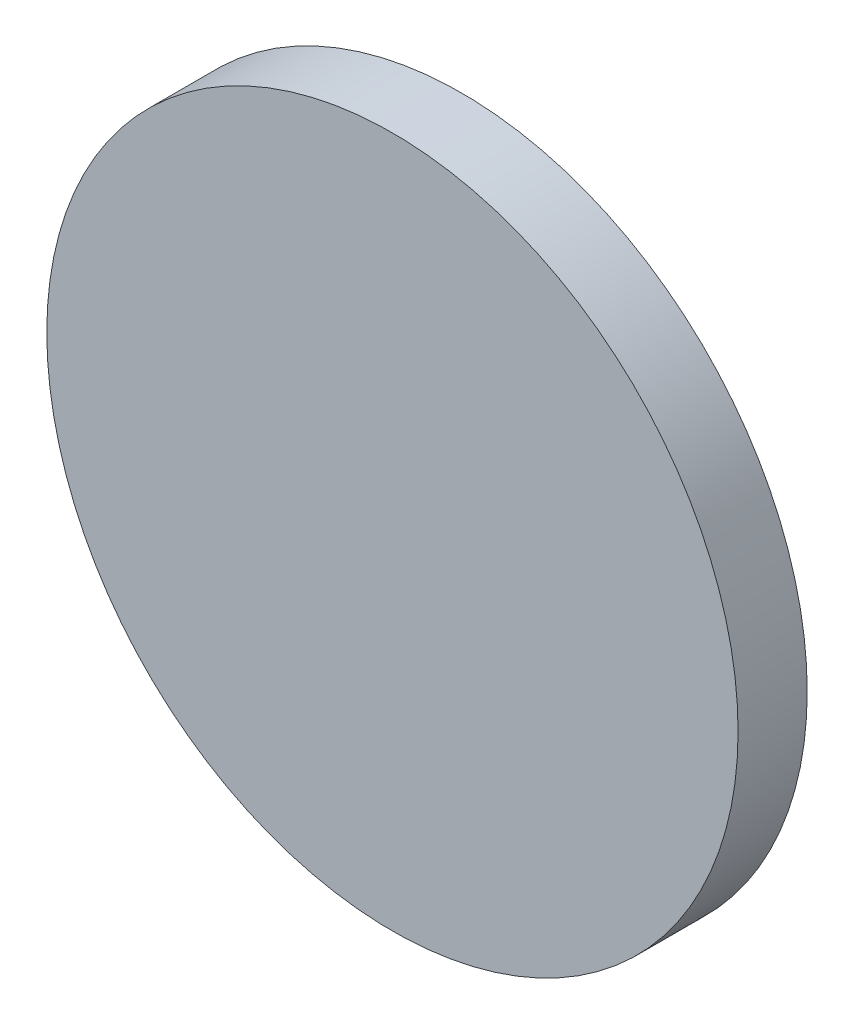
SolidWorks part; units mm, degrees
material "ABS"
ref_plane "Front" through (0, 0, 0) normal (0, 0, 1) x (1, 0, 0)
ref_plane "Top" through (0, 0, 0) normal (0, 1, 0) x (1, 0, 0)
ref_plane "Right" through (0, 0, 0) normal (1, 0, 0) x (0, 0, -1)
sketch "Sketch2" plane through (0, 0, 0) normal (0, 0, 1) x (1, 0, 0)
  circle A0 centre (0, 0) radius 254
  dimension "D1" = 508
extrude "Boss-Extrude1" add sketch "Sketch2" along normal blind 50.8
